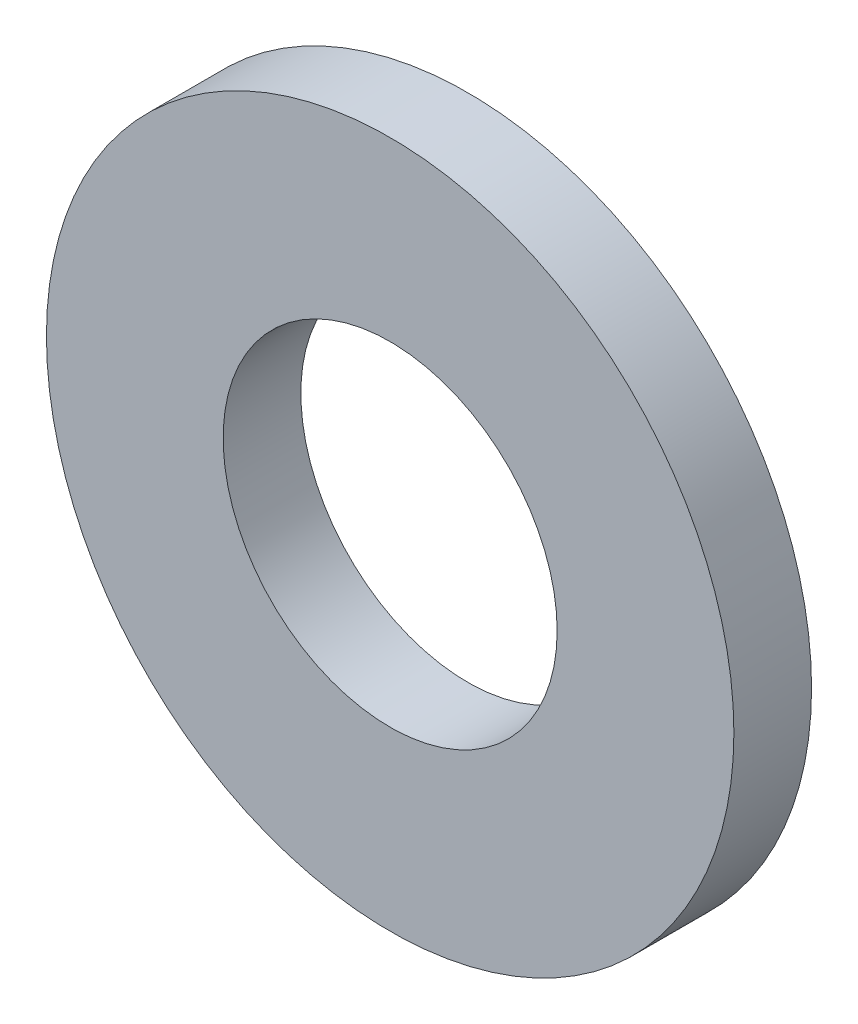
SolidWorks part; units mm, degrees
ref_plane "Front Plane" through (0, 0, 0) normal (0, 0, 1) x (1, 0, 0)
ref_plane "Top Plane" through (0, 0, 0) normal (0, 1, 0) x (1, 0, 0)
ref_plane "Right Plane" through (0, 0, 0) normal (1, 0, 0) x (0, 0, -1)
sketch "Sketch1" plane through (0, 0, 0) normal (0, 0, 1) x (1, 0, 0)
  circle A0 centre (0, 0) radius 4.425
  circle A1 centre (0, 0) radius 2.15
  dimension "D1" = 8.85
  dimension "D2" = 4.3
extrude "Boss-Extrude1" add sketch "Sketch1" along normal blind 1 contours A0
